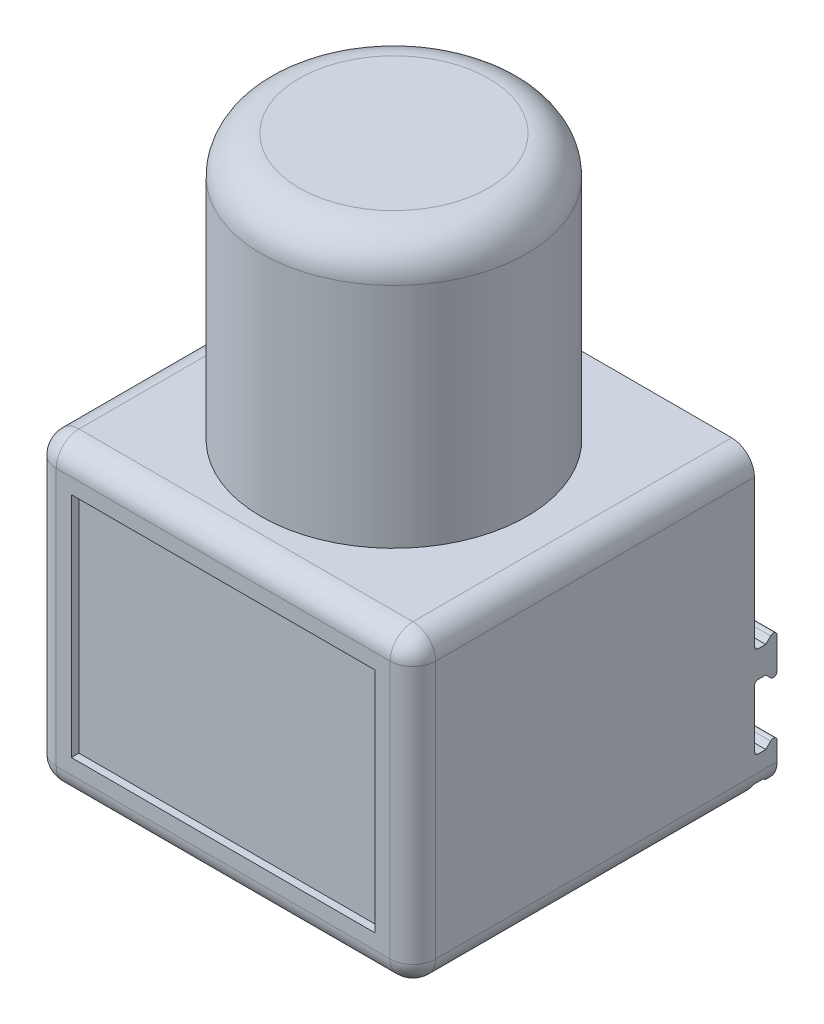
SolidWorks part; units mm, degrees
ref_plane "前视基准面" through (0, 0, 0) normal (0, 0, 1) x (1, 0, 0)
ref_plane "上视基准面" through (0, 0, 0) normal (0, 1, 0) x (1, 0, 0)
ref_plane "右视基准面" through (0, 0, 0) normal (1, 0, 0) x (0, 0, -1)
other "Configuration Table"
sketch "Sketch1" plane through (0, 0, 0) normal (0, 1, 0) x (1, 0, 0)
  line L1 (-250, -225) -> (250, -225)
  line L2 (-250, -225) -> (-250, 225)
  line L3 (-250, 225) -> (250, 225)
  line L4 (250, -225) -> (250, 225)
  line L5 (-250, -225) -> (250, 225) construction
  line L6 (-250, 225) -> (250, -225) construction
  point P0 (0, 0)
  dimension "D1" = 450
  dimension "D2" = 500
extrude "Boss-Extrude1" add sketch "Sketch1" along normal mid plane 400
sketch "Sketch2" plane through (250, 0, 0) normal (1, 0, 0) x (0, 0, -1)
  line L0 (225, -45.8423) -> (205, -45.8423) construction
  line L1 (225, 200) -> (225, -200) construction
  line L3 (225, -165.8423) -> (255, -165.8423) construction
  line L13 (240, -63.3423) -> (255, -78.3423)
  line L14 (255, -78.3423) -> (255, -13.3423)
  line L15 (255, -13.3423) -> (240, -28.3423)
  line L16 (240, -28.3423) -> (225, -28.3423)
  line L17 (225, -28.3423) -> (225, -63.3423)
  line L18 (225, -63.3423) -> (240, -63.3423)
  line L19 (225, -183.3423) -> (225, -148.3423)
  line L20 (225, -148.3423) -> (240, -148.3423)
  line L21 (240, -183.3423) -> (225, -183.3423)
  line L22 (255, -198.3423) -> (240, -183.3423)
  line L23 (255, -133.3423) -> (255, -198.3423)
  line L24 (240, -148.3423) -> (255, -133.3423)
  dimension "D1" = 120
  dimension "D3" = 35
  dimension "D4" = 30
  dimension "D5" = 15
  dimension "D2" = 45
  dimension "D6" = 45
extrude "Boss-Extrude2" add sketch "Sketch2" against normal up to surface (500 mm away) up to face at (-250, 0, 0)
fillet "Fillet1" radius 5 8 edges at (0, -198.3423, -255) (0, -183.3423, -225) (0, -133.3423, -255) (0, -148.3423, -225) (0, -63.3423, -225) (0, -78.3423, -255) (0, -13.3423, -255) (0, -28.3423, -225)
sketch "Sketch3" plane through (0, -200, 0) normal (0, -1, 0) x (1, 0, 0)
  circle A0 centre (0, 0) radius 150
  dimension "D1" = 300
extrude "Cut-Extrude1" cut sketch "Sketch3" against normal blind 200
sketch "Sketch4" plane through (0, 200, 0) normal (0, 1, 0) x (1, 0, 0)
  circle A0 centre (0, 0) radius 175
  dimension "D1" = 350
extrude "Boss-Extrude3" add sketch "Sketch4" along normal blind 350
fillet "Fillet2" radius 50 1 edges at (0, 550, 175)
fillet "Fillet3" radius 30 8 edges at (-250, 0, 225) (-250, -200, 0) (0, -200, 225) (250, -200, 0) (250, 0, 225) (250, 200, 0) (0, 200, 225) (-250, 200, 0)
sketch "Sketch5" plane through (0, 0, 225) normal (0, 0, 1) x (1, 0, 0)
  line L18 (-200, -150) -> (200, -150)
  line L19 (200, -150) -> (200, 150)
  line L20 (-200, 150) -> (-200, -150)
  line L21 (200, 150) -> (-200, 150)
  line L22 (-200, -150) -> (200, -150)
  line L23 (200, -150) -> (200, 150)
  line L24 (-200, 150) -> (-200, -150)
  line L25 (200, 150) -> (-200, 150)
  dimension "D1" = 20
extrude "Cut-Extrude2" cut sketch "Sketch5" against normal blind 10
